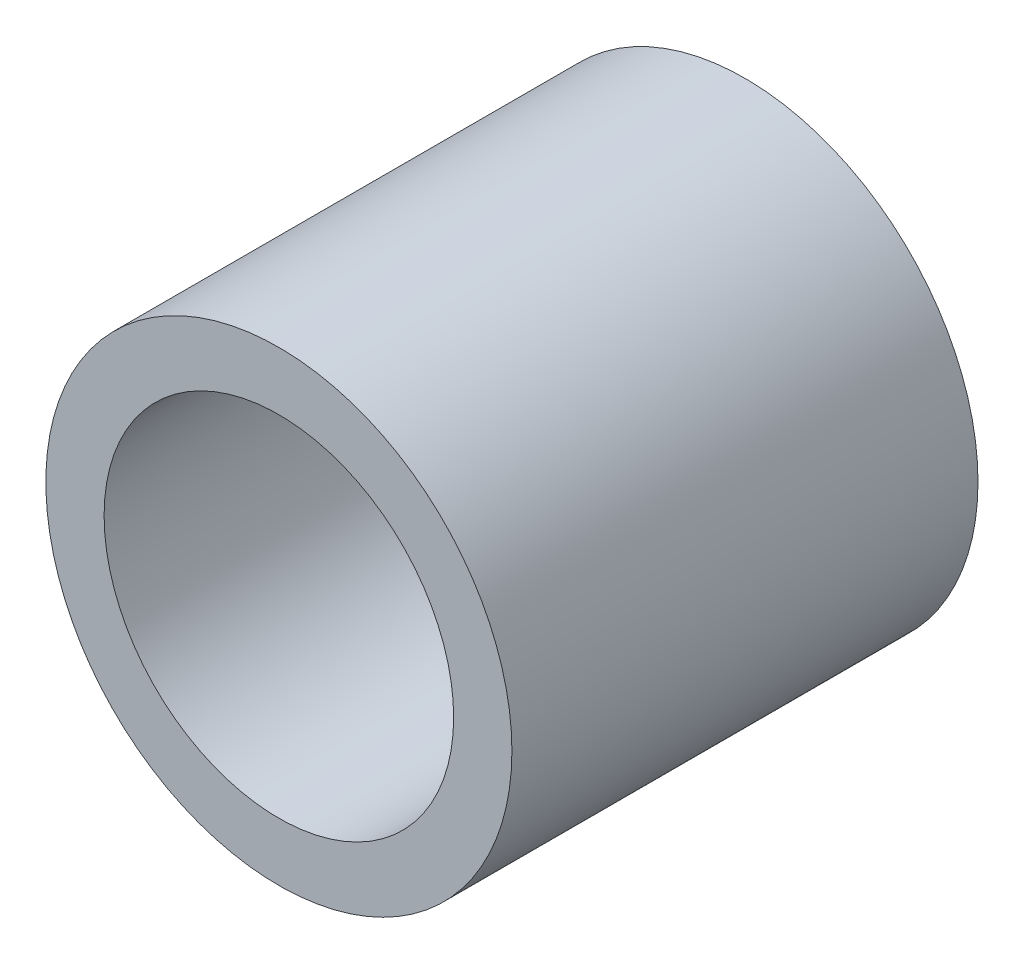
SolidWorks part; units mm, degrees
material "Alloy Steel"
ref_plane "Front Plane" through (0, 0, 0) normal (0, 0, 1) x (1, 0, 0)
ref_plane "Top Plane" through (0, 0, 0) normal (0, 1, 0) x (1, 0, 0)
ref_plane "Right Plane" through (0, 0, 0) normal (1, 0, 0) x (0, 0, -1)
sketch "Sketch2" plane through (0, 0, 0) normal (0, 0, 1) x (1, 0, 0)
  circle A0 centre (0, 0) radius 9.525
  circle A1 centre (0, 0) radius 12.7
  dimension "D1" = 19.05
  dimension "D2" = 25.4
extrude "Boss-Extrude1" add sketch "Sketch2" along normal mid plane 25.4
